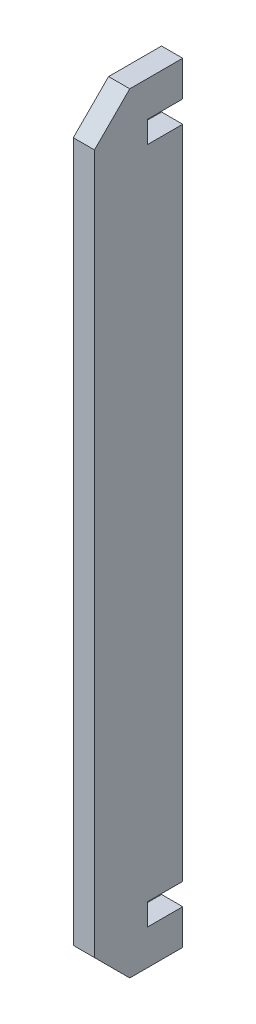
SolidWorks part; units mm, degrees
ref_plane "Front Plane" through (0, 0, 0) normal (1, 0, 0) x (0, 1, 0)
ref_plane "Top Plane" through (0, 0, 0) normal (0, 0, 1) x (0, 1, 0)
ref_plane "Right Plane" through (0, 0, 0) normal (0, 1, 0) x (-1, 0, 0)
sketch "Sketch1" plane through (0, 0, 0) normal (1, 0, 0) x (0, 1, 0)
  line L0 (-17.9216, 5.2239) -> (74.9784, 5.2239)
  line L1 (-26.0216, 0.2239) -> (83.0784, 0.2239)
  line L2 (-26.0216, 0.2239) -> (-26.0216, 12.7239)
  line L3 (-26.0216, 12.7239) -> (83.0784, 12.7239)
  line L4 (83.0784, 0.2239) -> (83.0784, 12.7239)
  line L5 (-21.0216, 0.2239) -> (-17.9216, 0.2239)
  line L6 (-21.0216, 0.2239) -> (-21.0216, 5.2239)
  line L7 (-21.0216, 5.2239) -> (-17.9216, 5.2239)
  line L8 (-17.9216, 0.2239) -> (-17.9216, 5.2239)
  line L9 (74.9784, 0.2239) -> (78.0784, 0.2239)
  line L10 (74.9784, 0.2239) -> (74.9784, 5.2239)
  line L11 (74.9784, 5.2239) -> (78.0784, 5.2239)
  line L12 (78.0784, 0.2239) -> (78.0784, 5.2239)
  line L13 (28.5284, 5.2239) -> (28.5284, 0.2239)
  dimension "D1" = 12.5
  dimension "D2" = 3.1
  dimension "D3" = 3.1
  dimension "D4" = 92.9
  dimension "D5" = 5
  dimension "D6" = 5
  dimension "D7" = 109.1
extrude "Boss-Extrude1" add sketch "Sketch1" along normal blind 3 contours L12 L1 L4 L3 L2 L6 L7 L0 L11 | L13 L0 L8 L1 | L0 L13 L1 L10
chamfer "Chamfer1" distance 5 angle 45 2 edges at (1.5, 83.0784, 12.7239) (1.5, -26.0216, 12.7239)
